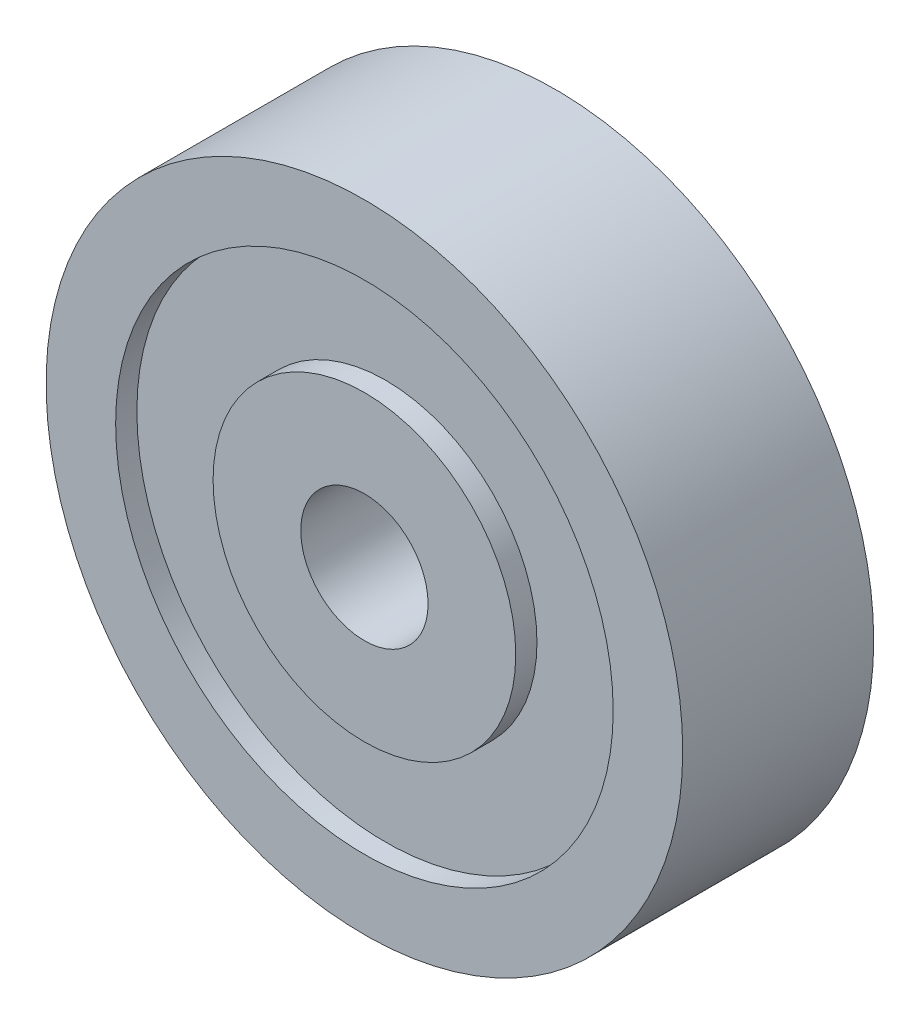
SolidWorks part; units mm, degrees
ref_plane "前视基准面" through (0, 0, 0) normal (0, 0, 1) x (1, 0, 0)
ref_plane "上视基准面" through (0, 0, 0) normal (0, 1, 0) x (1, 0, 0)
ref_plane "右视基准面" through (0, 0, 0) normal (1, 0, 0) x (0, 0, -1)
sketch "草图1" plane through (0, 0, 0) normal (0, 0, 1) x (1, 0, 0)
  circle A0 centre (0, 0) radius 3
  circle A1 centre (0, 0) radius 15
  dimension "D1" = 6
  dimension "D2" = 30
extrude "凸台-拉伸1" add sketch "草图1" along normal blind 9
sketch "草图2" plane through (0, 0, 0) normal (0, 0, -1) x (-1, 0, 0)
  circle A0 centre (0, 0) radius 7.1316
  circle A1 centre (0, 0) radius 11.7231
extrude "切除-拉伸1" cut sketch "草图2" against normal blind 1
ref_plane "基准面1" through (0, 0, 4.5) normal (0, 0, -1) x (-1, 0, 0)
mirror "镜向1" about plane through (0, 0, 4.5) normal (0, 0, -1) of "切除-拉伸1"
